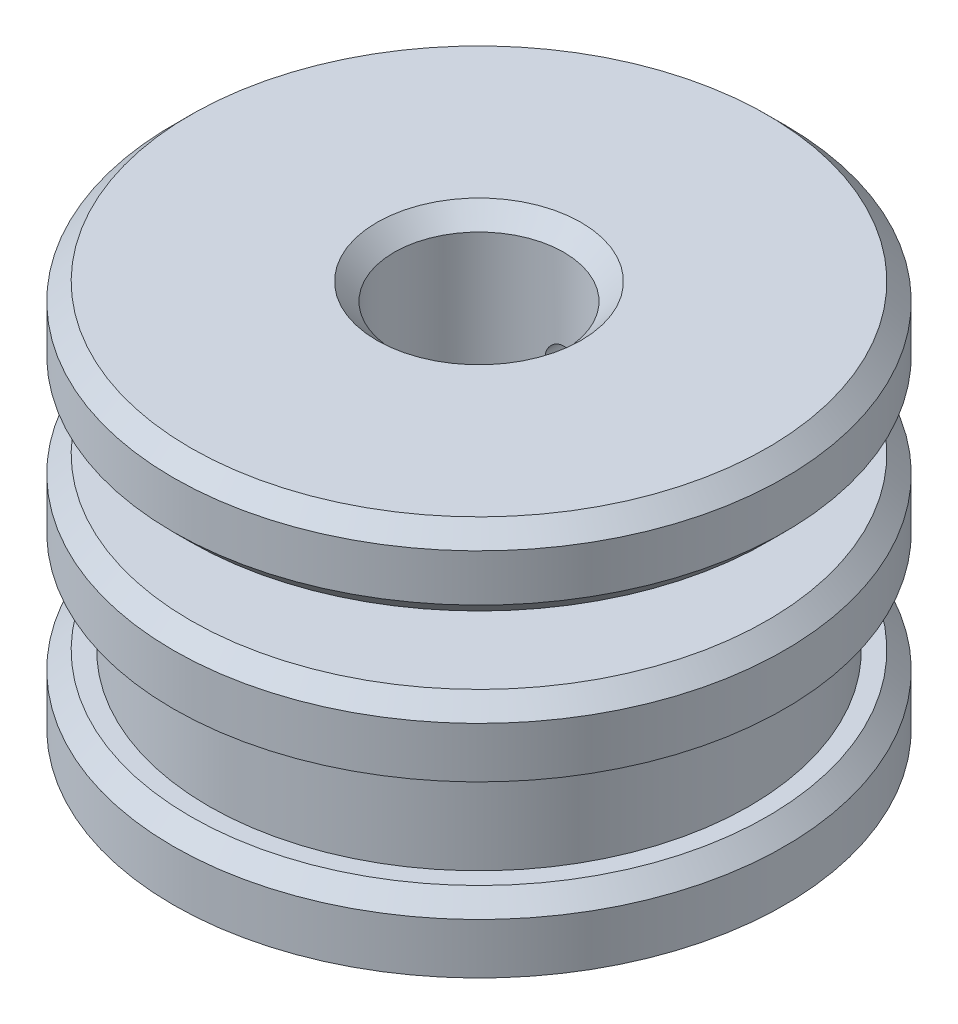
SolidWorks part; units mm, degrees
ref_plane "Front Plane" through (0, 0, 0) normal (0, 0, 1) x (1, 0, 0)
ref_plane "Top Plane" through (0, 0, 0) normal (0, 1, 0) x (1, 0, 0)
ref_plane "Right Plane" through (0, 0, 0) normal (1, 0, 0) x (0, 0, -1)
sketch "Sketch1" plane through (0, 0, 0) normal (0, 1, 0) x (1, 0, 0)
  circle A0 centre (0, 0) radius 2.35
  circle A1 centre (0, 0) radius 9
  dimension "D1" = 4.7
  dimension "D2" = 18
extrude "Boss-Extrude1" add sketch "Sketch1" along normal blind 2
sketch "Sketch2" plane through (0, 2, 0) normal (0, 1, 0) x (1, 0, 0)
  circle A0 centre (0, 0) radius 1.1375
  circle A1 centre (0, 0) radius 7.9615
  dimension "D1" = 2.275
  dimension "D2" = 15.923
extrude "Boss-Extrude2" add sketch "Sketch2" along normal blind 1.5
sketch "Sketch3" plane through (0, 3.5, 0) normal (0, 1, 0) x (1, 0, 0)
  circle A0 centre (0, 0) radius 7.9615
  circle A1 centre (0, 0) radius 2.5
  circle A2 centre (0, 0) radius 7.9615 construction
  dimension "D1" = 5
extrude "Boss-Extrude3" add sketch "Sketch3" along normal blind 1.5
sketch "Sketch5" plane through (0, 5, 0) normal (0, 1, 0) x (1, 0, 0)
  circle A0 centre (0, 0) radius 2.5
  circle A1 centre (0, 0) radius 9
  circle A2 centre (0, 0) radius 9 construction
  circle A3 centre (0, 0) radius 2.5 construction
extrude "Boss-Extrude4" add sketch "Sketch5" along normal blind 2
sketch "Sketch6" plane through (0, 7, 0) normal (0, 1, 0) x (1, 0, 0)
  circle A0 centre (0, 0) radius 2.5
  circle A1 centre (0, 0) radius 5.1
  circle A2 centre (0, 0) radius 2.5 construction
  dimension "D1" = 10.2
extrude "Boss-Extrude5" add sketch "Sketch6" along normal blind 2
sketch "Sketch7" plane through (0, 9, 0) normal (0, 1, 0) x (1, 0, 0)
  circle A0 centre (0, 0) radius 2.5
  circle A1 centre (0, 0) radius 9
  circle A2 centre (0, 0) radius 9 construction
  circle A3 centre (0, 0) radius 2.5 construction
extrude "Boss-Extrude6" add sketch "Sketch7" along normal blind 2.4
sketch "Sketch8" plane through (0, 0, 0) normal (0, 0, 1) x (1, 0, 0)
  line L0 (0, 0) -> (0, 2) construction
  line L1 (0, 2) -> (0, 5) construction
  line L2 (0, 5) -> (0, 7) construction
  line L3 (0, 7) -> (0, 9) construction
  line L4 (7.9615, 2) -> (-7.9615, 2) construction
  line L5 (-7.9615, 5) -> (7.9615, 5) construction
  line L6 (5.1, 7) -> (-5.1, 7) construction
  line L7 (-5.1, 9) -> (5.1, 9) construction
  circle A0 centre (0, 8) radius 0.5
  circle A1 centre (0, 4) radius 0.5
  dimension "D1" = 1
  dimension "D2" = 1
  dimension "D4" = 2
  dimension "D3" = 1
extrude "Cut-Extrude1" cut sketch "Sketch8" against normal through all
chamfer "Chamfer1" distance 0.508 angle 45 5 edges at (0, 11.4, 9) (0, 11.4, 2.5) (0, 2, 9) (0, 7, 9) (0, 9, 9)
